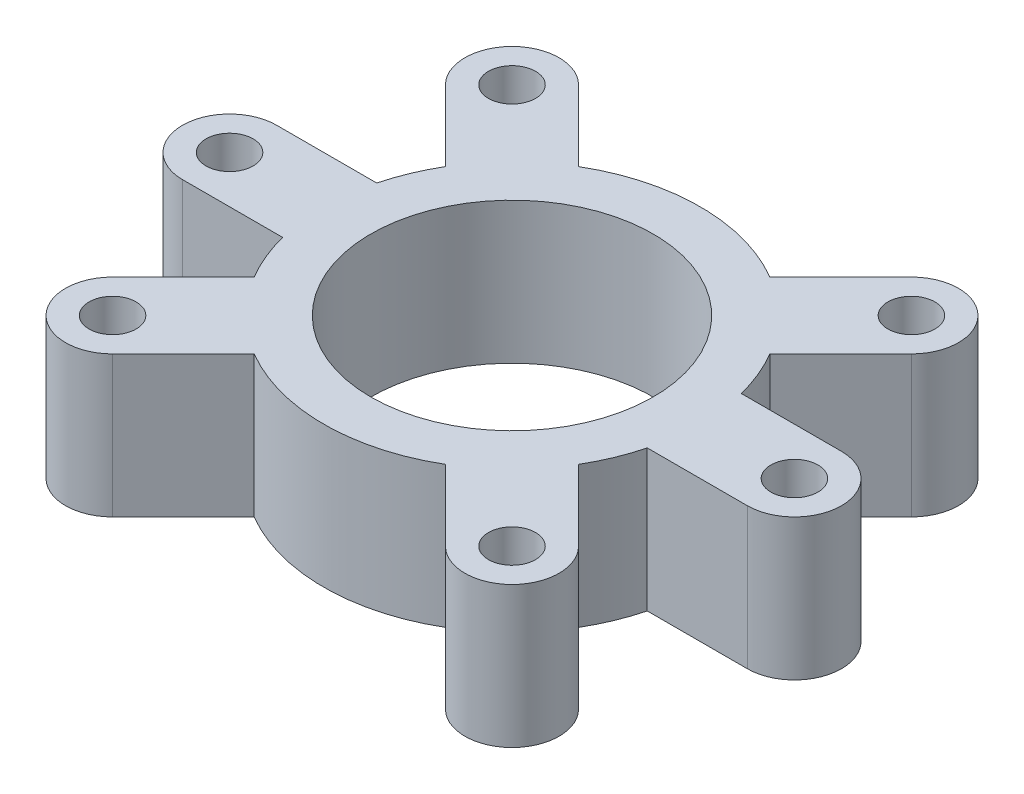
SolidWorks part; units mm, degrees
ref_plane "Front Plane" through (0, 0, 0) normal (0, 0, 1) x (1, 0, 0)
ref_plane "Top Plane" through (0, 0, 0) normal (0, 1, 0) x (1, 0, 0)
ref_plane "Right Plane" through (0, 0, 0) normal (1, 0, 0) x (0, 0, -1)
sketch "Sketch2" plane through (0, 0, 0) normal (0, 1, 0) x (1, 0, 0)
  line L0 (0, 0) -> (0, -5904.0573) construction
  line L1 (0, 0) -> (-5904.0573, 0) construction
  line L2 (38.7298, 10) -> (60, 10)
  line L3 (60, -10) -> (38.7298, -10)
  line L4 (34.4572, -20.3151) -> (49.4975, -35.3553)
  line L5 (35.3553, -49.4975) -> (20.3151, -34.4572)
  line L8 (-20.3151, -34.4572) -> (-35.3553, -49.4975)
  line L9 (-49.4975, -35.3553) -> (-34.4572, -20.3151)
  line L10 (-38.7298, -10) -> (-60, -10)
  line L11 (-60, 10) -> (-38.7298, 10)
  line L12 (-34.4572, 20.3151) -> (-49.4975, 35.3553)
  line L13 (-35.3553, 49.4975) -> (-20.3151, 34.4572)
  line L16 (20.3151, 34.4572) -> (35.3553, 49.4975)
  line L17 (49.4975, 35.3553) -> (34.4572, 20.3151)
  line L18 (10, 60) -> (10, 59.1608) [skipped]
  line L19 (-10, 59.1608) -> (-10, 60) [skipped]
  line L20 (10, -59.1608) -> (10, -59.9736) [skipped]
  line L21 (-10, -59.1608) -> (-10, -38.7298) [skipped]
  circle A0 centre (0, 0) radius 30
  arc A1 (-20.3151, -34.4572) -> (20.3151, -34.4572) centre (0, 0) ccw
  circle A2 centre (0, 0) radius 60 construction
  arc A3 (60, 10) -> (60, -10) centre (60, 0) cw
  circle A4 centre (60, 0) radius 5
  arc A5 (49.4975, -35.3553) -> (35.3553, -49.4975) centre (42.4264, -42.4264) cw
  circle A6 centre (42.4264, -42.4264) radius 5
  circle A7 centre (0, 0) radius 60 construction
  arc A8 (34.4572, -20.3151) -> (38.7298, -10) centre (0, 0) ccw
  circle A10 centre (0, 0) radius 60 construction
  arc A11 (-35.3553, -49.4975) -> (-49.4975, -35.3553) centre (-42.4264, -42.4264) cw
  circle A12 centre (-42.4264, -42.4264) radius 5
  circle A13 centre (0, 0) radius 60 construction
  arc A14 (-60, -10) -> (-60, 10) centre (-60, 0) cw
  circle A15 centre (-60, 0) radius 5
  circle A16 centre (0, 0) radius 60 construction
  arc A17 (-49.4975, 35.3553) -> (-35.3553, 49.4975) centre (-42.4264, 42.4264) cw
  circle A18 centre (-42.4264, 42.4264) radius 5
  circle A19 centre (0, 0) radius 60 construction
  arc A20 (38.7298, 10) -> (34.4572, 20.3151) centre (0, 0) ccw
  circle A22 centre (0, 0) radius 60 construction
  arc A23 (35.3553, 49.4975) -> (49.4975, 35.3553) centre (42.4264, 42.4264) cw
  circle A24 centre (42.4264, 42.4264) radius 5
  circle A25 centre (0, 0) radius 60 construction
  arc A26 (-10, 60) -> (0, 70) centre (0, 60) cw [skipped]
  arc A27 (0, 65) -> (-4.9957, 59.7917) centre (0, 60) ccw [skipped]
  arc A28 (4.9957, -59.7917) -> (0, -55) centre (0, -60) ccw [skipped]
  arc A29 (0, -70) -> (-10, -60) centre (0, -60) cw [skipped]
  arc A30 (20.3151, 34.4572) -> (-20.3151, 34.4572) centre (0, 0) ccw
  arc A31 (-34.4572, 20.3151) -> (-38.7298, 10) centre (0, 0) ccw
  arc A32 (-38.7298, -10) -> (-34.4572, -20.3151) centre (0, 0) ccw
  point P67 (0, 0)
  dimension "D1" = 60
  dimension "D2" = 80
  dimension "D3" = 120
  dimension "D4" = 10
  dimension "D5" = 10
  dimension "D6" = 8
extrude "Boss-Extrude1" add sketch "Sketch2" along normal mid plane 30
